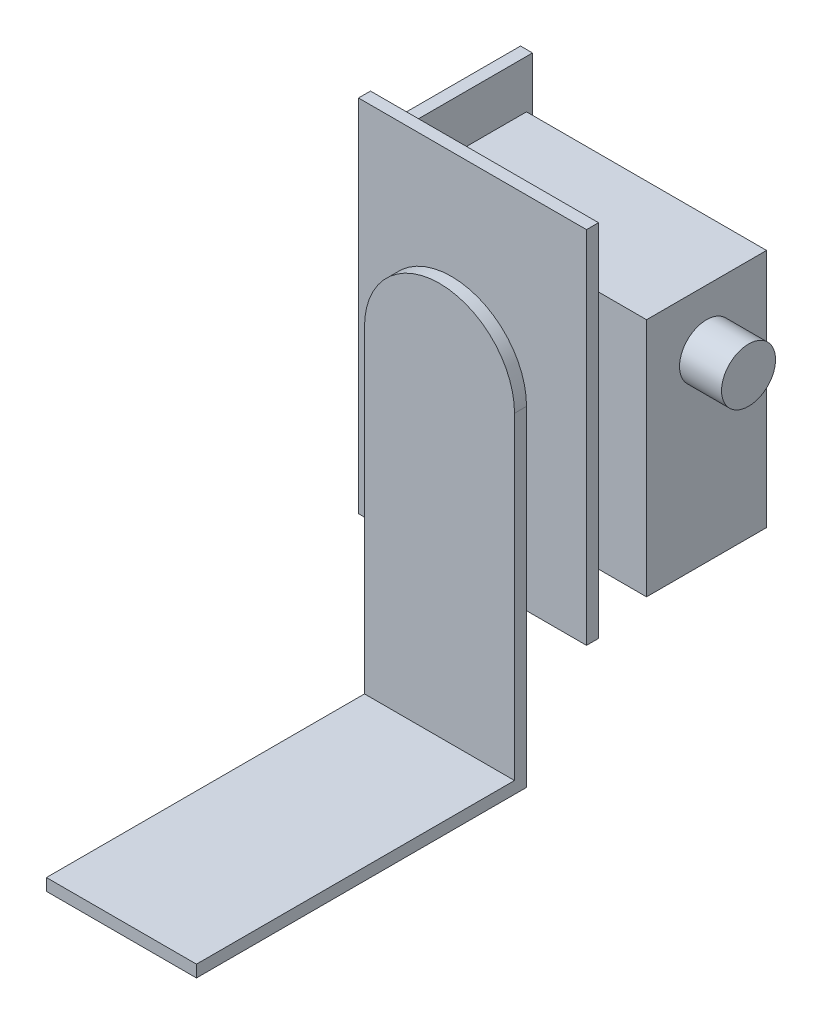
SolidWorks part; units mm, degrees
ref_plane "Plan de face" through (0, 0, 0) normal (0, 0, 1) x (1, 0, 0)
ref_plane "Plan de dessus" through (0, 0, 0) normal (0, 1, 0) x (1, 0, 0)
ref_plane "Plan de droite" through (0, 0, 0) normal (1, 0, 0) x (0, 0, -1)
sketch "Esquisse1" plane through (0, 0, 0) normal (0, 1, 0) x (1, 0, 0)
  line L1 (0, 0) -> (25, 0)
  line L2 (0, 0) -> (0, 55)
  line L3 (0, 55) -> (25, 55)
  line L4 (25, 0) -> (25, 55)
  dimension "D1" = 55
  dimension "D2" = 25
extrude "Boss.-Extru.1" add sketch "Esquisse1" along normal blind 2
sketch "Esquisse2" plane through (0, 2, 0) normal (0, 1, 0) x (1, 0, 0)
  line L0 (25, 0) -> (25, 55) construction
  line L1 (0, 55) -> (25, 55)
  line L2 (0, 55) -> (0, 53)
  line L3 (0, 53) -> (25, 53)
  line L4 (25, 55) -> (25, 53)
  dimension "D1" = 2
extrude "Boss.-Extru.2" add sketch "Esquisse2" along normal blind 53
sketch "Esquisse3" plane through (0, 0, -53) normal (0, 0, 1) x (1, 0, 0)
  line L0 (0, 55) -> (25, 55) construction
  line L1 (25, 55) -> (25, 2) construction
  line L6 (0, 2) -> (25, 2)
  line L7 (25, 2) -> (25, 55)
  line L8 (25, 55) -> (0, 55)
  line L9 (0, 55) -> (0, 2)
  line L10 (0, 2) -> (25, 2)
  line L11 (25, 2) -> (25, 55)
  line L13 (0, 55) -> (0, 2)
  arc A0 (0, 55) -> (25, 55) centre (12.5, 55) cw
  dimension "D1" = 0
extrude "Boss.-Extru.3" add sketch "Esquisse3" against normal blind 2
sketch "Esquisse5" plane through (0, 0, -53) normal (0, 0, 1) x (1, 0, 0)
  arc A0 (25, 55) -> (0, 55) centre (12.5, 55) ccw construction
  point P0 (12.5, 55)
sketch "Esquisse6" plane through (0, 0, -55) normal (0, 0, -1) x (-1, 0, 0)
  line L0 (-25, 55) -> (-25, 2) construction
  line L1 (-35, 25.5) -> (3, 25.5)
  line L2 (-35, 25.5) -> (-35, 85.5)
  line L3 (-35, 85.5) -> (3, 85.5)
  line L4 (3, 25.5) -> (3, 85.5)
  arc A0 (0, 55) -> (-25, 55) centre (-12.5, 55) ccw construction
  point P7 (-12.5, 67.5)
  dimension "D1" = 18
  dimension "D2" = 10
  dimension "D3" = 38
  dimension "D4" = 60
extrude "Boss.-Extru.4" add sketch "Esquisse6" along normal blind 2
sketch "Esquisse7" plane through (0, 0, -57) normal (0, 0, -1) x (-1, 0, 0)
  line L0 (-35, 85.5) -> (-35, 25.5) construction
  line L1 (-43, 35.5) -> (-3, 35.5)
  line L2 (-43, 35.5) -> (-43, 75.5)
  line L3 (-43, 75.5) -> (-3, 75.5)
  line L4 (-3, 35.5) -> (-3, 75.5)
  line L5 (3, 85.5) -> (-35, 85.5) construction
  dimension "D1" = 40
  dimension "D2" = 40
  dimension "D3" = 8
  dimension "D4" = 10
extrude "Boss.-Extru.5" add sketch "Esquisse7" along normal blind 20
sketch "Esquisse8" plane through (43, 0, 0) normal (1, 0, 0) x (0, 0, -1)
  line L1 (77, 75.5) -> (57, 75.5) construction
  line L2 (77, 75.5) -> (77, 35.5) construction
  circle A0 centre (67, 66) radius 4.5
  dimension "D1" = 9
  dimension "D2" = 9.5
  dimension "D3" = 10
sketch "Esquisse9" plane through (0, 0, -57) normal (0, 0, -1) x (-1, 0, 0)
  line L0 (3, 25.5) -> (3, 85.5) construction
  line L1 (3, 79.5) -> (1, 79.5)
  line L2 (3, 79.5) -> (3, 39.5)
  line L3 (3, 39.5) -> (1, 39.5)
  line L4 (1, 79.5) -> (1, 39.5)
  line L5 (3, 85.5) -> (-35, 85.5) construction
  point P6 (2, 79.5)
  dimension "D1" = 40
  dimension "D2" = 6
  dimension "D3" = 2
extrude "Boss.-Extru.6" add sketch "Esquisse9" along normal blind 25
extrude "Boss.-Extru.7" add sketch "Esquisse8" along normal blind 7
